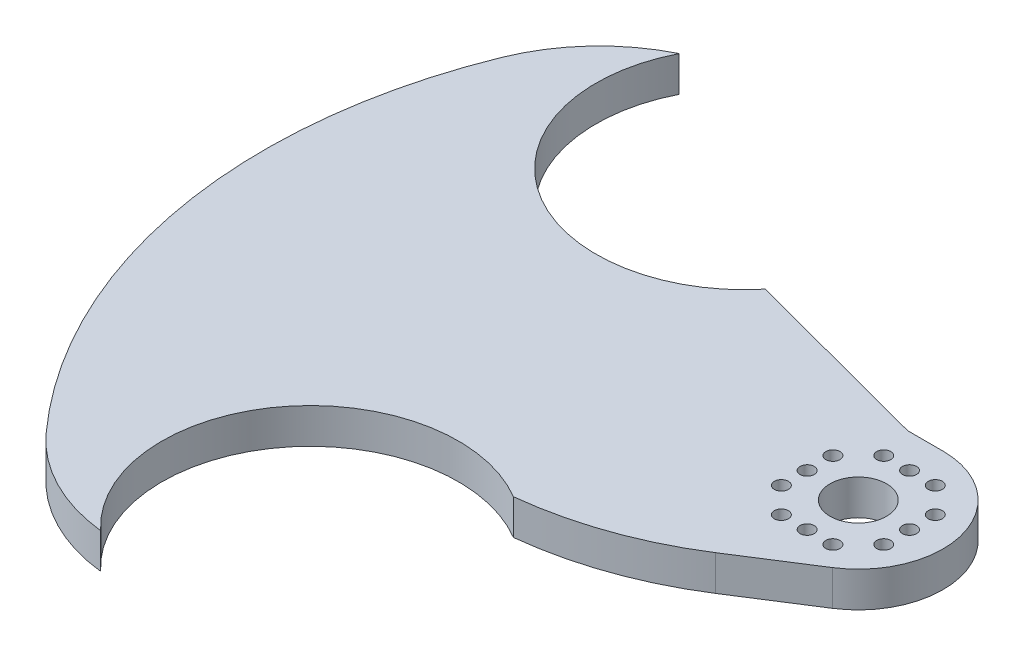
SolidWorks part; units mm, degrees
ref_plane "Plan de face" through (0, 0, 0) normal (0, 0, 1) x (1, 0, 0)
ref_plane "Plan de dessus" through (0, 0, 0) normal (0, 1, 0) x (1, 0, 0)
ref_plane "Plan de droite" through (0, 0, 0) normal (1, 0, 0) x (0, 0, -1)
sketch "Esquisse1" plane through (0, 0, 0) normal (0, 1, 0) x (1, 0, 0)
  line L0 (7.25, 3.65) -> (7.25, -3.65) construction
  line L1 (0, 0) -> (7.25, 0) construction
  line L2 (-32.4568, 19.2754) -> (-5, 12)
  line L3 (0, 12) -> (-5, 12)
  line L5 (-3.6645, -16.5702) -> (6.4529, -10.1173)
  line L12 (0, 0) -> (-85, 0) construction
  line L13 (-47.1515, -32.5563) -> (-56.3596, 19.6659) construction
  line L14 (-60, 0) -> (-47.1515, -32.5563) construction
  arc A0 (-24.8237, -24.0141) -> (-3.6645, -16.5702) centre (-30.1781, 25) ccw
  arc A3 (-11.0081, 29.8987) -> (-13.7897, -27.8365) centre (-10.0084, 0.9159) ccw construction
  circle A4 centre (0, 0) radius 4
  circle A5 centre (7.25, -3.65) radius 1
  circle A6 centre (7.25, 0) radius 1
  circle A7 centre (7.25, 3.65) radius 1
  circle A8 centre (3.65, -7.25) radius 1
  circle A9 centre (0, -7.25) radius 1
  circle A10 centre (-3.65, -7.25) radius 1
  circle A11 centre (-7.25, -3.65) radius 1
  circle A12 centre (-7.25, 0) radius 1
  circle A13 centre (-7.25, 3.65) radius 1
  circle A14 centre (-3.65, 7.25) radius 1
  circle A15 centre (0, 7.25) radius 1
  circle A16 centre (3.65, 7.25) radius 1
  arc A36 (-56.3596, 19.6659) -> (-47.1515, -32.5563) centre (-10.0084, 0.9159) ccw construction
  arc A37 (-79.5353, 29.0409) -> (-65.723, -49.2925) centre (-10.0084, 0.9159) ccw
  arc A40 (-65.723, -49.2925) -> (-49.8954, -57.4053) centre (-47.1515, -32.5563) ccw
  arc A41 (6.4529, -10.1173) -> (0, 12) centre (0, 0) ccw
  arc A42 (-10.0859, 50.9159) -> (-41.1378, -38.2116) centre (-10.0084, 0.9159) ccw construction
  arc A43 (-67.437, 42.0778) -> (-32.4568, 19.2754) centre (-48.7125, 32.5702) ccw
  arc A44 (-67.437, 42.0778) -> (-79.5353, 29.0409) centre (-56.3596, 19.6659) ccw
  arc A45 (-24.8237, -24.0141) -> (-49.8954, -57.4053) centre (-35.5519, -42.0669) ccw
  point P39 (0, 0)
  point P78 (-56.6847, 2.6915)
  point P85 (-60, 0)
  dimension "D4" = 25
  dimension "D5" = 12
  dimension "D6" = 21
  dimension "D7" = 25
  dimension "D8" = 25
  dimension "D9" = 7.25
  dimension "D10" = 5
  dimension "D18" = 85
  dimension "D20" = 75
  dimension "D26" = 12
  dimension "D13" = 50
  dimension "D14" = 21
  dimension "D15" = 7.3
  dimension "D22" = 35
  dimension "D23" = 100
  dimension "D24" = 20
  dimension "D25" = 25
  dimension "D30" = 15
  dimension "D32" = 15
extrude "Boss.-Extru.1" add sketch "Esquisse1" along normal blind 5
